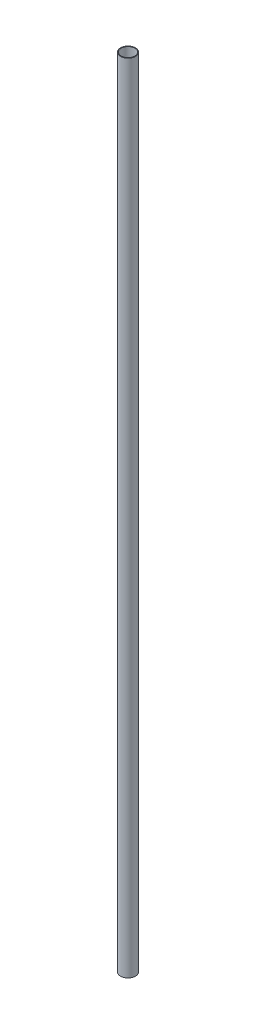
SolidWorks part; units mm, degrees
ref_plane "Front Plane" through (0, 0, 0) normal (0, 0, 1) x (1, 0, 0)
ref_plane "Top Plane" through (0, 0, 0) normal (0, 1, 0) x (1, 0, 0)
ref_plane "Right Plane" through (0, 0, 0) normal (1, 0, 0) x (0, 0, -1)
sketch "Sketch1" plane through (0, 0, 0) normal (0, 1, 0) x (1, 0, 0)
  circle A0 centre (0, 0) radius 9.525
  dimension "D1" = 19.05
extrude "Extrude1" add sketch "Sketch1" along normal blind 1016
sketch "Sketch2" plane through (0, 0, 0) normal (0, 1, 0) x (1, 0, 0)
  circle A0 centre (0, 0) radius 8.636
  dimension "D1" = 17.272
extrude "Cut-Extrude1" cut sketch "Sketch2" along normal blind 1016
